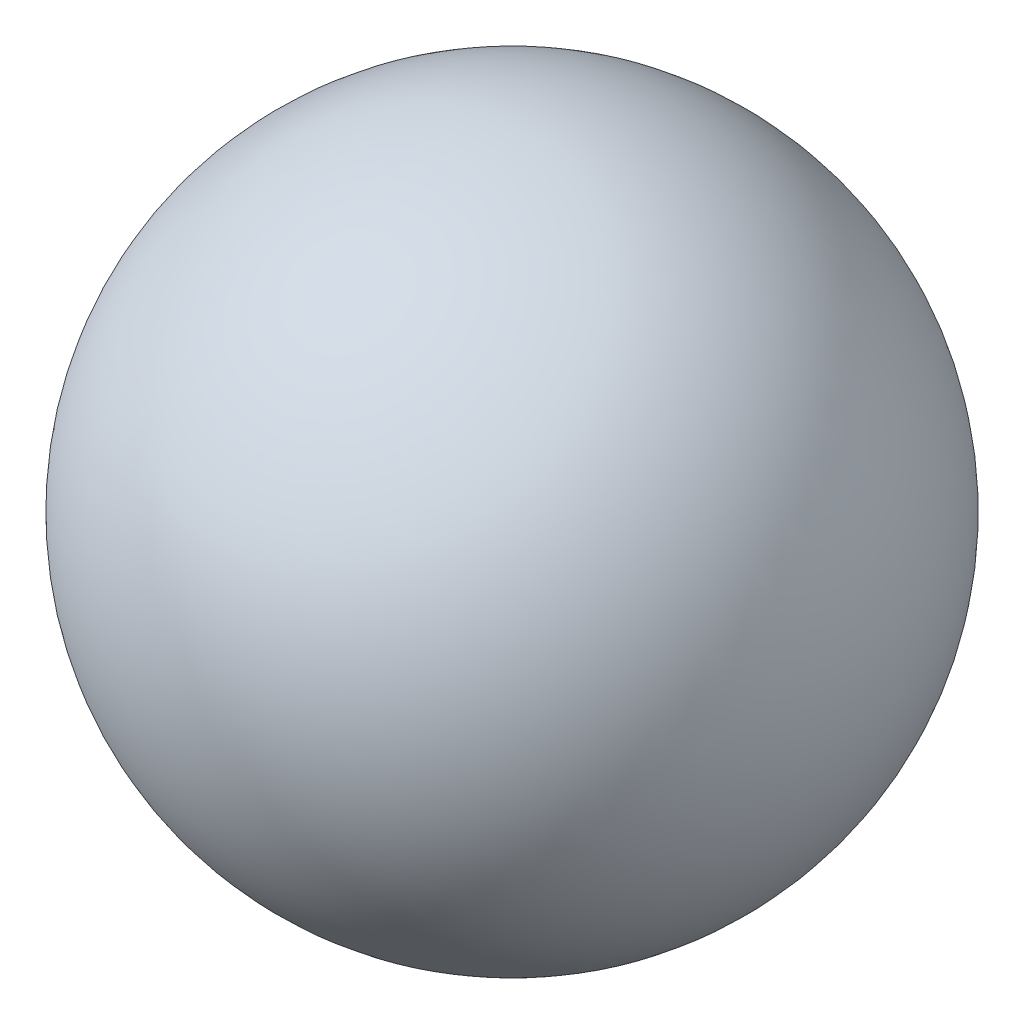
SolidWorks part; units mm, degrees
material "Cast Alloy Steel"
ref_plane "Front Plane" through (0, 0, 0) normal (0, 0, 1) x (1, 0, 0)
ref_plane "Top Plane" through (0, 0, 0) normal (0, 1, 0) x (1, 0, 0)
ref_plane "Right Plane" through (0, 0, 0) normal (1, 0, 0) x (0, 0, -1)
sketch "Sketch1" plane through (0, 0, 0) normal (0, 0, 1) x (1, 0, 0)
  line L0 (0, 4.7625) -> (0, -4.7625)
  arc A0 (0, 4.7625) -> (0, -4.7625) centre (0, 0) cw
  point P3 (0, 0)
  dimension "D1" = 9.525
revolve "Revolve1" add sketch "Sketch1" angle 360 about L0
